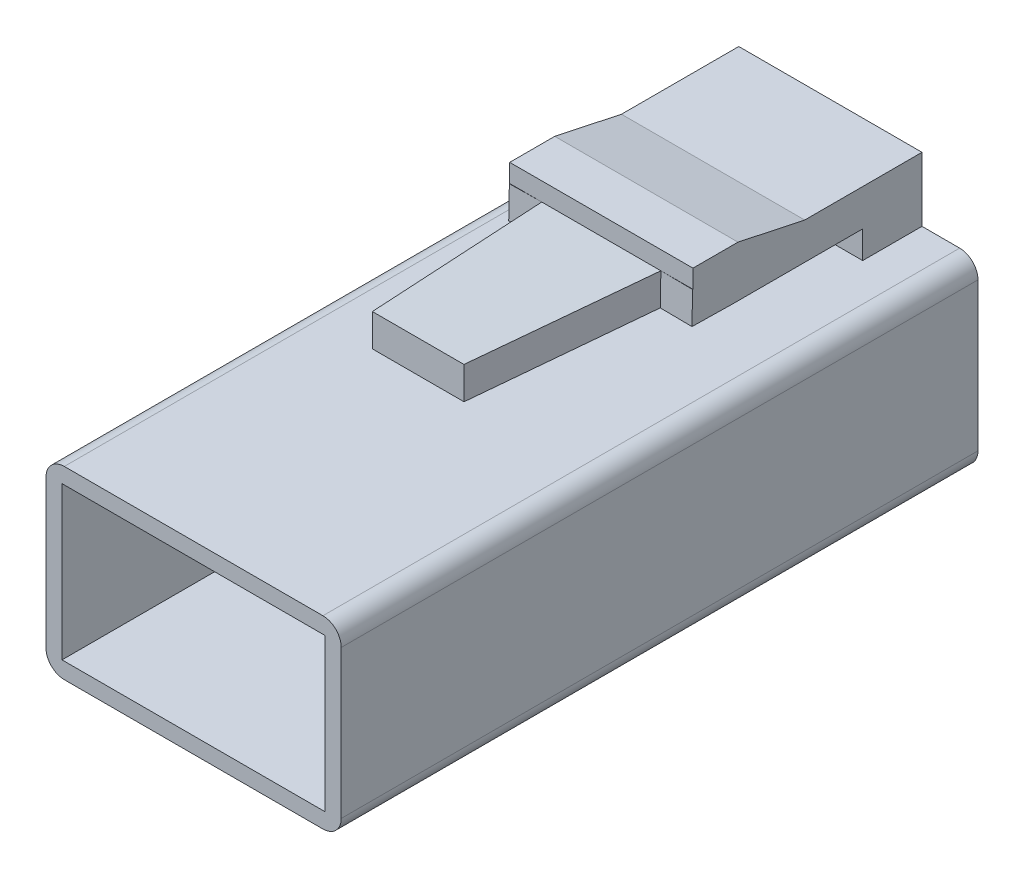
SolidWorks part; units mm, degrees
material "Nickel"
ref_plane "Front Plane" through (0, 0, 0) normal (0, 0, 1) x (1, 0, 0)
ref_plane "Top Plane" through (0, 0, 0) normal (0, 1, 0) x (1, 0, 0)
ref_plane "Right Plane" through (0, 0, 0) normal (1, 0, 0) x (0, 0, -1)
sketch "Sketch2" plane through (0, 0, 0) normal (0, 0, 1) x (1, 0, 0)
  line L1 (2.2725, -1.066) -> (-2.2725, -1.066)
  line L2 (2.2725, -1.066) -> (2.2725, 1.066)
  line L3 (2.2725, 1.066) -> (-2.2725, 1.066)
  line L4 (-2.2725, -1.066) -> (-2.2725, 1.066)
  line L5 (2.2725, -1.066) -> (-2.2725, 1.066) construction
  line L6 (2.2725, 1.066) -> (-2.2725, -1.066) construction
  line L7 (3.2225, -2.016) -> (-3.2225, -2.016)
  line L8 (3.2225, -2.016) -> (3.2225, 2.016)
  line L9 (3.2225, 2.016) -> (-3.2225, 2.016)
  line L10 (-3.2225, -2.016) -> (-3.2225, 2.016)
  line L11 (3.2225, -2.016) -> (-3.2225, 2.016) construction
  line L12 (3.2225, 2.016) -> (-3.2225, -2.016) construction
  point P0 (0, 0)
  point P7 (0, 0)
  dimension "D1" = 2.132
  dimension "D2" = 4.545
  dimension "D3" = 0.95
  dimension "D4" = 0.95
extrude "Boss-Extrude1" add sketch "Sketch2" against normal blind 3.9 and the other way blind 10
sketch "Sketch3" plane through (0, 0, 0) normal (0, 0, 1) x (1, 0, 0)
  line L0 (-2.8725, -1.666) -> (-2.8725, 1.666)
  line L1 (2.8725, 1.666) -> (2.8725, -1.666)
  line L2 (2.8725, -1.666) -> (-2.8725, -1.666)
  line L3 (-2.8725, 1.666) -> (2.8725, 1.666)
  line L4 (2.2725, 1.066) -> (-2.2725, 1.066) construction
  line L5 (-2.2725, -1.066) -> (2.2725, -1.066) construction
  line L6 (-2.2725, 1.066) -> (-2.2725, -1.066) construction
  line L7 (2.2725, -1.066) -> (2.2725, 1.066) construction
  dimension "D1" = 0.6
  dimension "D2" = 0.6
  dimension "D3" = 0.6
  dimension "D4" = 0.6
extrude "Cut-Extrude1" cut sketch "Sketch3" along normal up to surface (10 mm away) up to face at (0, 0, 10)
fillet "Fillet1" radius 0.4 4 edges at (3.2225, -2.016, 3.05) (3.2225, 2.016, 3.05) (-3.2225, -2.016, 3.05) (-3.2225, 2.016, 3.05)
sketch "Sketch6" plane through (0, 0, 0) normal (1, 0, 0) x (0, 0, -1)
  line L0 (3.9, 2.016) -> (3.9001, 2.016)
  line L1 (3.9001, 2.016) -> (3.9001, 3.416)
  line L2 (3.9001, 3.416) -> (1.3399, 3.416)
  line L3 (1.3399, 3.416) -> (-0.1172, 3.726)
  line L4 (-0.1172, 3.726) -> (-1.1, 3.726)
  line L5 (-1.1, 3.726) -> (-1.1, 3.326)
  line L6 (-1.1, 3.326) -> (-5.0985, 3.4049)
  line L7 (-5.0985, 3.4049) -> (-5.0985, 2.6991)
  line L8 (-5.0985, 2.6991) -> (-0.2168, 2.616)
  line L9 (-0.2168, 2.616) -> (2.6053, 2.616)
  line L10 (2.6053, 2.616) -> (2.6053, 2.016)
  line L11 (3.9, 2.016) -> (-10, 2.016) construction
  line L12 (2.6053, 2.016) -> (3.9, 2.016)
  line L13 (3.9, 1.616) -> (3.9, -1.616) construction
  line L14 (3.9, -1.616) -> (3.9, 1.616) construction
  point P3 (-6.877, 2.808)
  point P18 (-6.8589, 2.7263)
  point P21 (-5.2346, 2.7444)
  point P22 (-5.0985, 2.6991)
  dimension "D1" = 0.4
  dimension "D2" = 1.4
  dimension "D3" = 0.8
  dimension "D4" = 0.0001
  dimension "D5" = 0.31
  dimension "D6" = 5
extrude "Boss-Extrude2" add sketch "Sketch6" along normal blind 2 and the other way blind 2
sketch "Sketch7" plane through (0, 3.303, -0.0652) normal (0, 0.9998, -0.0197) x (1, 0, 0)
  line L0 (0, -1.1654) -> (0, -5.1646) construction
  line L1 (-2, -1.1654) -> (2, -1.1654) construction
  line L2 (-2, -5.1646) -> (2, -5.1646) construction
  line L4 (-1, -5.1646) -> (-1.3, -1.1654)
  line L5 (-1.3, -1.1654) -> (-2, -1.1733)
  line L6 (-2, -1.1733) -> (-2, -5.1646)
  line L7 (-2, -5.1646) -> (-1, -5.1646)
  line L8 (1, -5.1646) -> (1.3, -1.1654)
  line L9 (1.3, -1.1654) -> (2, -1.1733)
  line L10 (2, -1.1733) -> (2, -5.1646)
  line L11 (2, -5.1646) -> (1, -5.1646)
  point P9 (0, -8.4369)
  dimension "D1" = 0.7
  dimension "D2" = 1
extrude "Cut-Extrude2" cut sketch "Sketch7" against normal up to surface (0.7057 mm away)
